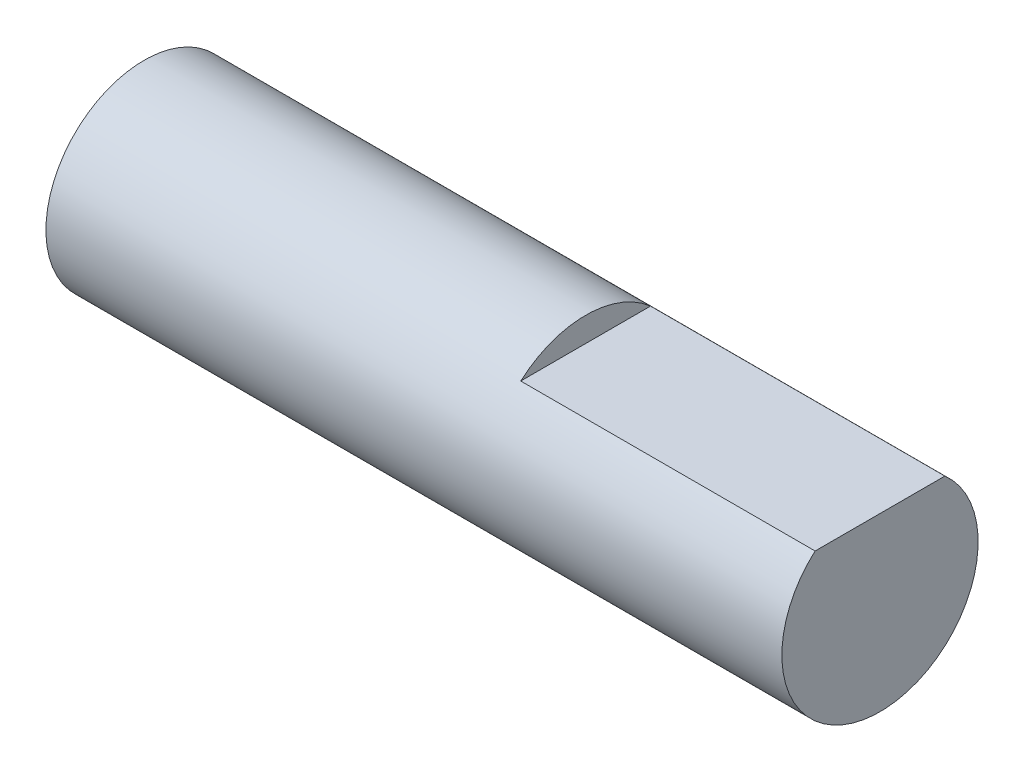
SolidWorks part; units mm, degrees
material "Alloy Steel"
ref_plane "Front Plane" through (0, 0, 0) normal (0, 0, 1) x (1, 0, 0)
ref_plane "Top Plane" through (0, 0, 0) normal (0, 1, 0) x (1, 0, 0)
ref_plane "Right Plane" through (0, 0, 0) normal (1, 0, 0) x (0, 0, -1)
sketch "Sketch1" plane through (0, 0, 0) normal (1, 0, 0) x (0, 0, -1)
  circle A0 centre (0, 0) radius 4
  dimension "D1" = 8
extrude "Boss-Extrude1" add sketch "Sketch1" along normal blind 30
sketch "Sketch2" plane through (30, 0, 0) normal (1, 0, 0) x (0, 0, -1)
  line L0 (-2.6458, 3) -> (2.6458, 3)
  circle A0 centre (0, 0) radius 4 construction
  arc A1 (-2.6458, 3) -> (2.6458, 3) centre (0, 0) cw
  dimension "D2" = 4
  dimension "D1" = 3
extrude "Cut-Extrude1" cut sketch "Sketch2" against normal blind 12
